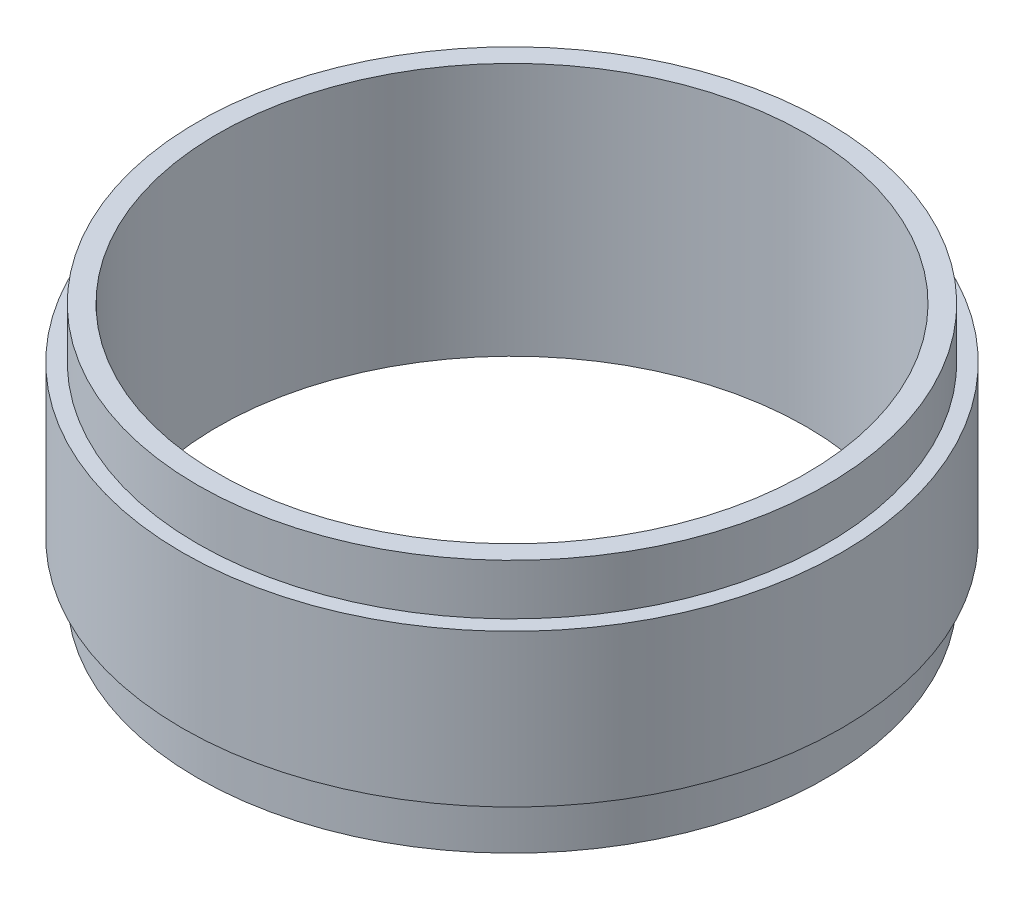
SolidWorks part; units mm, degrees
material "HYPALON"
ref_plane "Front Plane" through (0, 0, 0) normal (0, 0, 1) x (1, 0, 0)
ref_plane "Top Plane" through (0, 0, 0) normal (0, 1, 0) x (1, 0, 0)
ref_plane "Right Plane" through (0, 0, 0) normal (1, 0, 0) x (0, 0, -1)
sketch "Szkic1" plane through (0, 0, 0) normal (0, 0, 1) x (1, 0, 0)
  line L0 (0, 0) -> (-65, 0)
  line L1 (-65, 10) -> (-62, 10)
  line L3 (-58, 0) -> (-58, 50)
  line L4 (-62, 10) -> (-62, 0)
  line L5 (-58, 50) -> (-62, 50)
  line L7 (-65, 10) -> (-65, 40)
  line L8 (-65, 40) -> (-62, 40)
  line L9 (-62, 40) -> (-62, 50)
  line L13 (0, 0) -> (0, 22.4148)
  dimension "D1" = 65
  dimension "D2" = 10
  dimension "D3" = 7
  dimension "D4" = 50
  dimension "D5" = 3
  dimension "D7" = 3
  dimension "D8" = 10
revolve "Obrót1" add sketch "Szkic1" angle 360 about L13
